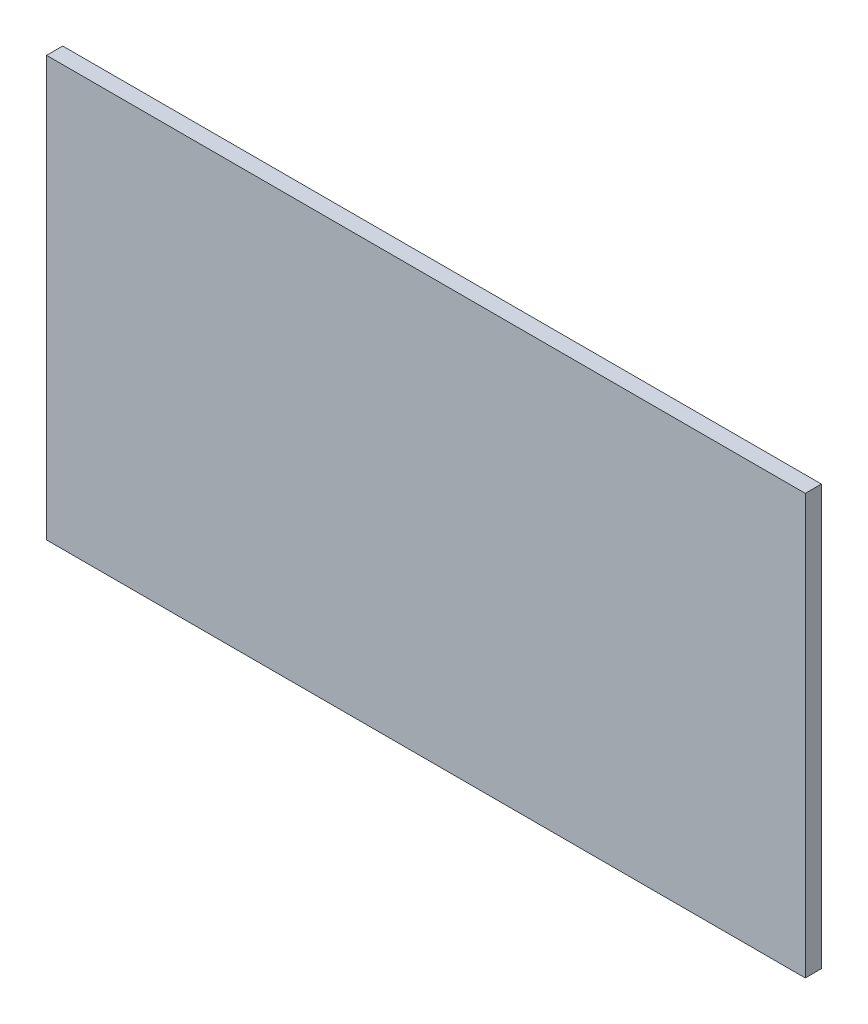
SolidWorks part; units mm, degrees
ref_plane "Front Plane" through (0, 0, 0) normal (0, 0, 1) x (1, 0, 0)
ref_plane "Top Plane" through (0, 0, 0) normal (0, 1, 0) x (1, 0, 0)
ref_plane "Right Plane" through (0, 0, 0) normal (1, 0, 0) x (0, 0, -1)
sketch "Sketch1" plane through (0, 0, 40.959) normal (0, 0, 1) x (1, 0, 0)
  line L1 (-3.8869, 13.703) -> (41.1131, 13.703)
  line L2 (-3.8869, 13.703) -> (-3.8869, 37.703)
  line L3 (-3.8869, 37.703) -> (41.1131, 37.703)
  line L4 (41.1131, 13.703) -> (41.1131, 37.703)
extrude "Boss-Extrude1" add sketch "Sketch1" against normal blind 1
sketch "Sketch2" plane through (0, 0, 40.959) normal (0, 0, 1) x (1, 0, 0)
  line L1 (-4.8869, 38.703) -> (42.1131, 38.703)
  line L2 (-4.8869, 38.703) -> (-4.8869, 12.703)
  line L3 (-4.8869, 12.703) -> (42.1131, 12.703)
  line L4 (42.1131, 38.703) -> (42.1131, 12.703)
extrude "Boss-Extrude2" add sketch "Sketch2" along normal blind 1
